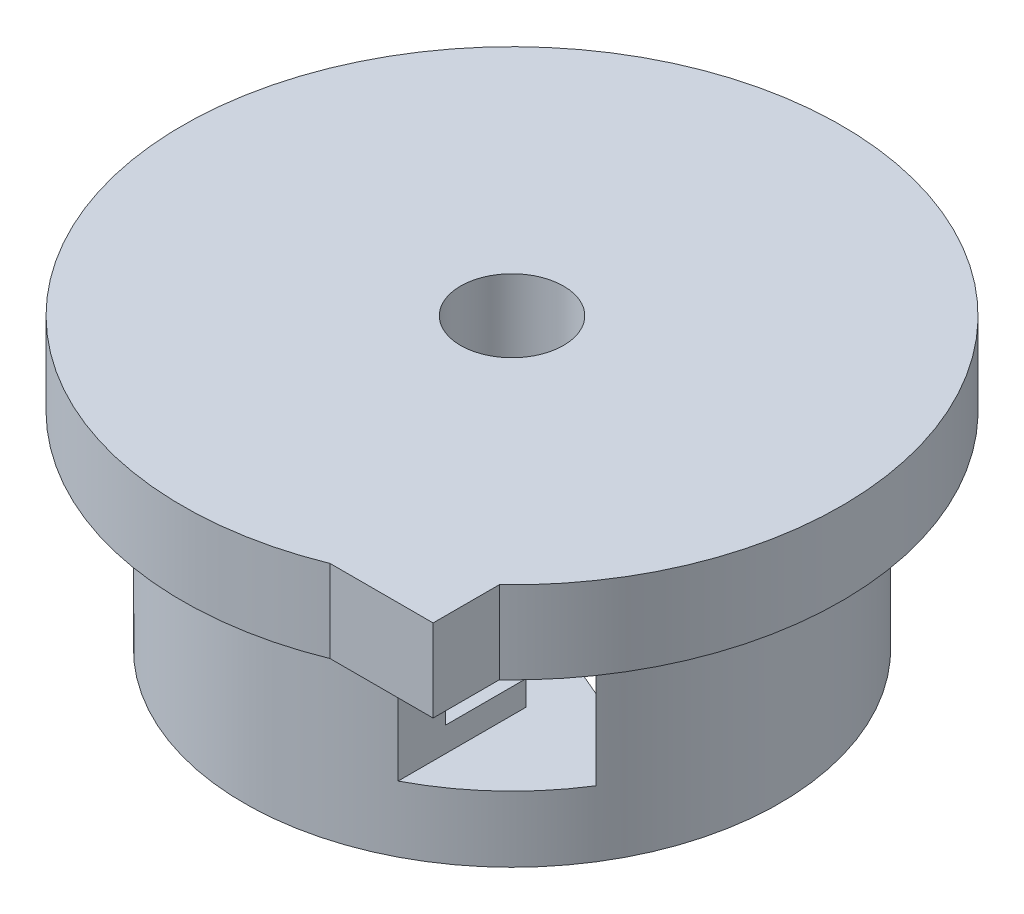
SolidWorks part; units mm, degrees
ref_plane "前视基准面" through (0, 0, 0) normal (0, 0, 1) x (1, 0, 0)
ref_plane "上视基准面" through (0, 0, 0) normal (0, 1, 0) x (1, 0, 0)
ref_plane "右视基准面" through (0, 0, 0) normal (1, 0, 0) x (0, 0, -1)
other "Configuration Table"
sketch "草图1" plane through (0, 0, 0) normal (0, 1, 0) x (1, 0, 0)
  circle A0 centre (0, 0) radius 12.5
  circle A1 centre (0, 0) radius 14.5
  dimension "D1" = 25
  dimension "D2" = 2
extrude "凸台-拉伸1" add sketch "草图1" along normal blind 40
sketch "草图2" plane through (0, 0, 0) normal (0, -1, 0) x (1, 0, 0)
  circle A0 centre (0, 0) radius 14.5
extrude "凸台-拉伸2" add sketch "草图2" along normal blind 3 from offset 3 offset against normal yes
sketch "草图3" plane through (0, 0, 0) normal (0, -1, 0) x (1, 0, 0)
  circle A0 centre (-4.8196, 8.1867) radius 1.1498
  circle A1 centre (9.4997, 0.0805) radius 1.1498
  circle A2 centre (-4.6801, -8.2672) radius 1.1498
  point P9 (0, 0)
  dimension "D1" = 9.5
  dimension "D2" = 3
hole_wizard "M3 螺纹孔1" positions "3D草图1" profile "草图4" tap size "M3" standard "GB" end condition through all
sketch3d "3D草图1"
  point P0 (-4.8196, 0, 8.1867)
  point P3 (-4.6801, 0, -8.2672)
  point P6 (9.4997, 0, 0.0805)
  point P9 (3.8445, 0, 49.8704)
sketch "草图4" plane through (-4.8196, 0, 8.1867) normal (1, 0, 0) x (0, 0, -1)
  line L0 (0, 0) -> (0, 40)
  line L1 (0, 40) -> (1.25, 40)
  line L2 (1.25, 40) -> (1.25, 0.2308)
  line L3 (1.25, 0.2308) -> (1.525, 0)
  line L5 (1.525, 0) -> (0, 0)
  line L6 (-1.25, 0.2308) -> (-1.525, 0) construction
  line L11 (0, -6.35) -> (0, 107.95) construction
  dimension "通孔螺纹孔钻头直径" = 2.5
  dimension "通孔螺纹孔钻头深度" = 40
  dimension "近端锥形沉头孔直径" = 3.05
  dimension "近端锥形沉头孔角度" = 100
cosmetic thread "孔螺蚊线6" parameters "D1"=12, "D2"=3.5
cosmetic thread "孔螺蚊线7" parameters "D1"=12, "D2"=3.5
cosmetic thread "孔螺蚊线8" parameters "D1"=12, "D2"=3.5
sketch "草图5" plane through (0, 0, 0) normal (0, -1, 0) x (1, 0, 0)
  circle A0 centre (0, 0) radius 6.5
  dimension "D1" = 13
extrude "切除-拉伸1" cut sketch "草图5" against normal through all both
sketch "草图6" plane through (0, 0, 0) normal (0, -1, 0) x (1, 0, 0)
  arc A6 (-7.4873, 7.3614) -> (-7.2233, -7.6206) centre (0, 0) ccw
sweep "切除-扫描1" cut path "草图6" circular profile diameter 4 parameters "D3"=4
pattern_circular "阵列(圆周)2" count 3 over 360 about axis through (0, 0, 0) along (0, 1, 0) of "切除-扫描1"
sketch "草图62" plane through (0, 0, 0) normal (0, -1, 0) x (1, 0, 0)
  circle A2 centre (0, 0) radius 10.5 construction
sketch "草图63" plane through (0, 40, 0) normal (0, 1, 0) x (1, 0, 0)
  circle A0 centre (0, 0) radius 80
  circle A1 centre (0, 0) radius 12.5 construction
  circle A2 centre (0, 0) radius 12.5
  dimension "D1" = 160
extrude "凸台-拉伸3" add sketch "草图63" along normal blind 20
sketch "草图64" plane through (0, 40, 0) normal (0, -1, 0) x (1, 0, 0)
  circle A0 centre (0, 0) radius 35
  dimension "D1" = 70
sweep "切除-扫描2" cut path "草图64" circular profile diameter 10 parameters "D3"=10
sketch "草图69" plane through (0, 40, 0) normal (0, -1, 0) x (1, 0, 0)
  line L0 (55, 0) -> (55, 34.641)
  line L1 (30, 46.0977) -> (30, 57.6628)
  line L2 (30, 0) -> (30, 76.0523) construction
  line L3 (55, 0) -> (55, 76.0523) construction
  arc A0 (30, 46.0977) -> (55, 0) centre (0, 0) ccw
  arc A3 (30, 57.6628) -> (55, 34.641) centre (0, 0) ccw
  circle A5 centre (0, 0) radius 65 construction
  circle A6 centre (0, 0) radius 55 construction
  dimension "D1" = 110
  dimension "D2" = 10
  dimension "D4" = 25
extrude "凸台-拉伸7" add sketch "草图69" along normal blind 50
sketch "草图73" plane through (0, -10, 0) normal (0, -1, 0) x (1, 0, 0)
  line L0 (30, 57.6628) -> (30, 26.6585)
  line L1 (30, 26.6585) -> (23.8833, 29.8408)
  line L2 (30, 57.6628) -> (39.154, 52.9003)
  line L3 (25.6781, 18.8754) -> (18.5721, 62.2903)
  line L4 (31.4074, 19.8132) -> (25.6781, 18.8754)
  arc A0 (30, 57.6628) -> (55, 34.641) centre (0, 0) ccw construction
  arc A1 (30, 57.6628) -> (55, 34.641) centre (0, 0) ccw construction
  arc A2 (30, 26.6585) -> (31.4074, 19.8132) centre (47.3508, 26.6585) ccw
  arc M1 (30, 57.6628) -> (55, 34.641) centre (0, 0) ccw
  arc M3 (55, 0) -> (30, 46.0977) centre (0, 0) cw
  line M4 (30, 46.0977) -> (30, 57.6628)
extrude "凸台-拉伸9" add sketch "草图73" against normal blind 22 contours L3 M3 M4 M1 | L3 L1 L0 M3
sketch "草图74" plane through (0, -10, 0) normal (0, -1, 0) x (1, 0, 0)
  line L0 (27.575, 11.8161) -> (59.7458, 25.6016)
  line L1 (24.1436, 60.3497) -> (11.1432, 27.8537)
  arc A0 (30, 57.6628) -> (55, 34.641) centre (0, 0) ccw construction
  arc A1 (59.7458, 25.6016) -> (24.1436, 60.3497) centre (0, 0) ccw
  arc A3 (27.575, 11.8161) -> (11.1432, 27.8537) centre (0, 0) ccw
  dimension "D1" = 45
extrude "凸台-拉伸10" add sketch "草图74" against normal blind 16
sketch "草图77" plane through (0, 0, 0) normal (1, 0, 0) x (0, 0, -1)
  line L3 (-34.8349, 8.0597) -> (-63.7469, 8.0597)
  line L6 (-63.7469, 8.0597) -> (-63.7469, -4.1085)
  line L7 (-63.7469, -4.1085) -> (-34.8349, -4.1085)
  line L8 (-34.8349, -4.1085) -> (-34.8349, 8.0597)
extrude "凸台-拉伸11" add sketch "草图77" along normal mid plane 1
ref_plane "基准面1" through (0, 15, 0) normal (0, -1, 0) x (-1, 0, 0)
ref_plane "基准面2" through (0, 20, 0) normal (0, -1, 0) x (-1, 0, 0)
sketch "草图83" plane through (0, 20, 0) normal (0, -1, 0) x (-1, 0, 0)
  line L0 (-55, -23.568) -> (-55, 0) construction
  line L1 (-55, -23.568) -> (-55, 0)
  arc A0 (-20.408, -51.0736) -> (-55, 0) centre (0, 0) ccw construction
  arc A1 (-20.408, -51.0736) -> (-55, 0) centre (0, 0) ccw
sweep "切除-扫描4" cut path "草图83" circular profile diameter 10 parameters "D3"=10
sketch "草图90" plane through (0, 40, 0) normal (0, -1, 0) x (1, 0, 0)
  line L0 (55, 34.641) -> (55, 58.0948)
  line L1 (30, 57.6628) -> (30, 74.162)
  line L2 (0, 0) -> (44.0312, 47.8147)
  circle A1 centre (0, 0) radius 65 construction
  arc A2 (55, 34.641) -> (30, 57.6628) centre (0, 0) ccw
  circle A3 centre (0, 0) radius 80 construction
  arc A4 (55, 58.0948) -> (30, 74.162) centre (0, 0) ccw
  circle M2 centre (0, 0) radius 80
extrude "切除-拉伸2" cut sketch "草图90" against normal blind 10 contours A2 L0 L1 M2
sketch "草图91" plane through (0, 40, 0) normal (0, -1, 0) x (1, 0, 0)
  line L0 (55, 58.0948) -> (55, 74.162)
  line L1 (55, 74.162) -> (30, 74.162)
  arc A0 (55, 58.0948) -> (30, 74.162) centre (0, 0) ccw construction
  arc A1 (55, 58.0948) -> (30, 74.162) centre (0, 0) ccw
extrude "凸台-拉伸12" add sketch "草图91" against normal blind 10 from offset 10 offset against normal yes
sketch "草图96" plane through (0, 50, 0) normal (0, -1, 0) x (1, 0, 0)
  line L4 (55, 34.641) -> (55, 58.0948)
  line L5 (55, 58.0948) -> (55, 74.162)
  line L6 (55, 74.162) -> (30, 74.162)
  line L7 (30, 74.162) -> (30, 57.6628)
  line L8 (55, 34.641) -> (55, 58.0948)
  line L9 (55, 58.0948) -> (55, 74.162)
  line L10 (55, 74.162) -> (30, 74.162)
  line L11 (30, 74.162) -> (30, 57.6628)
  arc A1 (55, 34.641) -> (30, 57.6628) centre (0, 0) ccw
  arc A2 (55, 34.641) -> (30, 57.6628) centre (0, 0) ccw
  dimension "D1" = 0
extrude "凸台-拉伸13" add sketch "草图96" along normal blind 10
